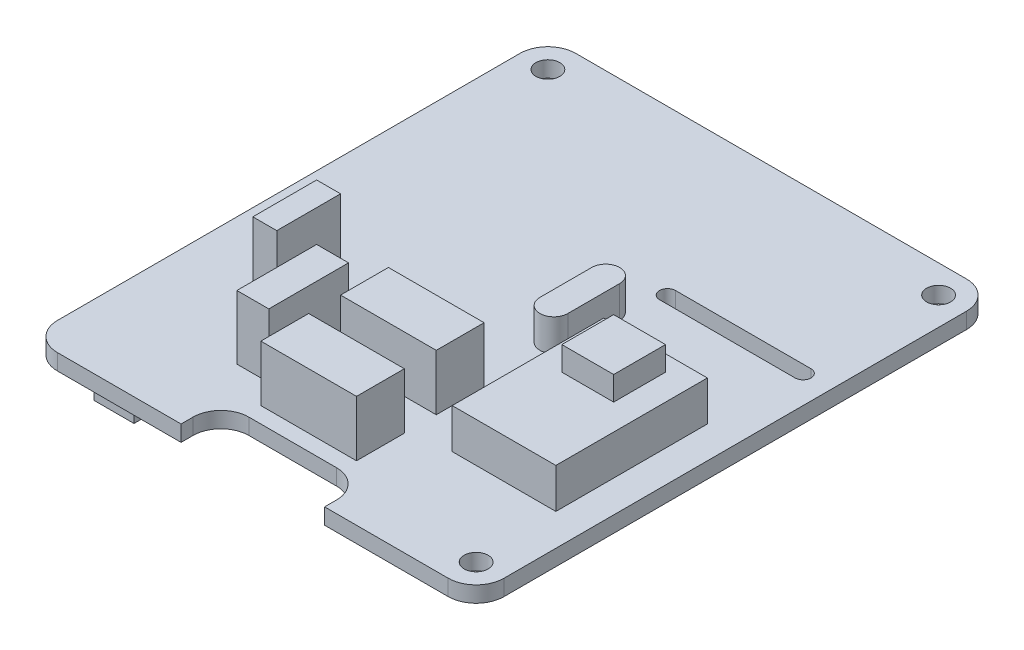
SolidWorks part; units mm, degrees
ref_plane "Спереди" through (0, 0, 0) normal (0, 0, 1) x (1, 0, 0)
ref_plane "Сверху" through (0, 0, 0) normal (0, 1, 0) x (1, 0, 0)
ref_plane "Справа" through (0, 0, 0) normal (1, 0, 0) x (0, 0, -1)
sketch "Эскиз1" plane through (0, 0, 0) normal (0, 1, 0) x (1, 0, 0)
  line L0 (0, 32.5) -> (0, -32.5) construction
  line L1 (-28, 32.5) -> (28, 32.5)
  line L2 (-28, 32.5) -> (-28, -32.5)
  line L3 (-28, -32.5) -> (-9, -32.5)
  line L4 (28, 32.5) -> (28, -32.5)
  line L5 (9, -32.5) -> (28, -32.5)
  line L6 (-28, 0) -> (28, 0) construction
  line L8 (-9, -32.5) -> (-9, -27.5)
  line L9 (-9, -27.5) -> (9, -27.5)
  line L10 (9, -32.5) -> (9, -27.5)
  point P4 (0, 0)
  point P14 (0, -27.5)
  dimension "D1" = 56
  dimension "D2" = 65
  dimension "D3" = 5
  dimension "D4" = 18
extrude "плата" add sketch "Эскиз1" along normal blind 2
sketch "Эскиз2" plane through (0, 2, 0) normal (0, 1, 0) x (1, 0, 0)
  line L0 (0, 32.5) -> (0, -27.5) construction
  line L1 (28, 32.5) -> (-28, 32.5) construction
  line L2 (-9, -27.5) -> (9, -27.5) construction
  line L3 (-28, 0) -> (28, 0) construction
  line L5 (-28, 32.5) -> (-28, -32.5) construction
  line L6 (28, -32.5) -> (28, 32.5) construction
  line L7 (-24.5, 29) -> (24.5, 29) construction
  line L8 (24.5, 29) -> (24.5, -29) construction
  circle A0 centre (-24.5, 29) radius 1.5
  circle A1 centre (24.5, 29) radius 1.5
  circle A2 centre (24.5, -29) radius 1.5
  point P18 (0, 29)
  point P19 (24.5, 0)
  dimension "D1" = 3
  dimension "D2" = 49
  dimension "D3" = 58
extrude "крепежные отверстия" cut sketch "Эскиз2" against normal through all
sketch "Эскиз3" plane through (0, 2, 0) normal (0, 1, 0) x (1, 0, 0)
  line L0 (7.5, 13) -> (24.5, 13)
  line L1 (7.5, 11) -> (24.5, 11)
  line L2 (7.5, 12) -> (24.5, 12) construction
  line L3 (24.5, 29) -> (24.5, 12) construction
  arc A0 (7.5, 13) -> (7.5, 11) centre (7.5, 12) ccw
  arc A1 (24.5, 11) -> (24.5, 13) centre (24.5, 12) ccw
  point P1 (6.5, 12)
  dimension "D2" = 1
  dimension "D1" = 18
  dimension "D3" = 17
extrude "отверстие для шлейфа" cut sketch "Эскиз3" against normal through all
sketch "Эскиз4" plane through (0, 0, 0) normal (0, -1, 0) x (1, 0, 0)
  line L0 (-24.5, -25.4) -> (-24.5, -29) construction
  line L1 (-27, 25.4) -> (-22, 25.4)
  line L2 (-27, 25.4) -> (-27, -25.4)
  line L3 (-27, -25.4) -> (-22, -25.4)
  line L4 (-22, 25.4) -> (-22, -25.4)
  point P8 (-24.5, -25.4)
  dimension "D1" = 5
  dimension "D2" = 50.8
  dimension "D3" = 3.6
extrude "гребенка" add sketch "Эскиз4" along normal blind 8
sketch "Эскиз5" plane through (0, 2, 0) normal (0, 1, 0) x (1, 0, 0)
  line L0 (0, -27.5) -> (0, -25.5) construction
  line L1 (-6, -19.5) -> (6, -19.5)
  line L2 (-6, -19.5) -> (-6, -25.5)
  line L3 (-6, -25.5) -> (6, -25.5)
  line L4 (6, -19.5) -> (6, -25.5)
  line L5 (-9, -27.5) -> (9, -27.5) construction
  dimension "D1" = 2
  dimension "D2" = 6
  dimension "D3" = 12
extrude "CAN разъем" add sketch "Эскиз5" along normal blind 7
pattern_linear "Линейный массив1" count 2 spacing 10 along (0, 0, -1) of "CAN разъем"
sketch "Эскиз6" plane through (0, 2, 0) normal (0, 1, 0) x (1, 0, 0)
  line L0 (-6, -15.5) -> (-6, -19.5) construction
  line L1 (-12, -12.5) -> (-8, -12.5)
  line L2 (-12, -12.5) -> (-12, -22.5)
  line L3 (-12, -22.5) -> (-8, -22.5)
  line L4 (-8, -12.5) -> (-8, -22.5)
  line L5 (-6, -17.5) -> (-8, -17.5) construction
  dimension "D1" = 2
  dimension "D2" = 4
  dimension "D3" = 10
extrude "терминатор" add sketch "Эскиз6" along normal blind 8
sketch "Эскиз7" plane through (0, 2, 0) normal (0, 1, 0) x (1, 0, 0)
  line L0 (9, -32.5) -> (28, -32.5) construction
  line L1 (11, 0.5) -> (24, 0.5)
  line L2 (11, 0.5) -> (11, -18.5)
  line L3 (11, -18.5) -> (24, -18.5)
  line L4 (24, 0.5) -> (24, -18.5)
  line L5 (28, -32.5) -> (28, 32.5) construction
  dimension "D1" = 13
  dimension "D2" = 19
  dimension "D3" = 14
  dimension "D4" = 4
extrude "преобразователь напряжения" add sketch "Эскиз7" along normal blind 5
sketch "Эскиз8" plane through (0, 7, 0) normal (0, 1, 0) x (1, 0, 0)
  line L0 (17.5, 0.5) -> (17.5, -18.5) construction
  line L1 (24, 0.5) -> (11, 0.5) construction
  line L2 (11, -18.5) -> (24, -18.5) construction
  line L3 (24, 0.5) -> (11, 0.5) construction
  line L4 (14.25, -1.5) -> (20.75, -1.5)
  line L5 (14.25, -1.5) -> (14.25, -8)
  line L6 (14.25, -8) -> (20.75, -8)
  line L7 (20.75, -1.5) -> (20.75, -8)
  point P10 (17.5, -1.5)
  dimension "D1" = 6.5
  dimension "D2" = 2
extrude "катушка преобразователя" add sketch "Эскиз8" along normal blind 3
sketch "Эскиз9" plane through (0, 2, 0) normal (0, 1, 0) x (1, 0, 0)
  line L0 (-28, -32.5) -> (-9, -32.5) construction
  line L1 (-19, -5.5) -> (-16, -5.5)
  line L2 (-19, -5.5) -> (-19, -13.5)
  line L3 (-19, -13.5) -> (-16, -13.5)
  line L4 (-16, -5.5) -> (-16, -13.5)
  line L5 (-28, 32.5) -> (-28, -32.5) construction
  dimension "D1" = 3
  dimension "D2" = 8
  dimension "D3" = 19
  dimension "D4" = 9
extrude "разъем uart" add sketch "Эскиз9" along normal blind 8
sketch "Эскиз10" plane through (0, 2, 0) normal (0, 1, 0) x (1, 0, 0)
  line L0 (3.75, -0.25) -> (3.75, 6.25)
  line L1 (7.25, -0.25) -> (7.25, 6.25)
  line L2 (5.5, 6.25) -> (5.5, -0.25) construction
  arc A0 (7.25, 6.25) -> (3.75, 6.25) centre (5.5, 6.25) ccw
  arc A1 (3.75, -0.25) -> (7.25, -0.25) centre (5.5, -0.25) ccw
  arc A2 (7.5, 13) -> (7.5, 11) centre (7.5, 12) ccw construction
  point P1 (5.5, 8)
  point P3 (5.5, -2)
  point P11 (6.5, 12)
  dimension "D1" = 3.5
  dimension "D2" = 10
  dimension "D3" = 1
  dimension "D4" = 4
extrude "кварц" add sketch "Эскиз10" along normal blind 4
fillet "Скругление1" radius 3.5 6 edges at (28, 1, -32.5) (-28, 1, -32.5) (-28, 1, 32.5) (-9, 1, 27.5) (9, 1, 27.5) (28, 1, 32.5)
